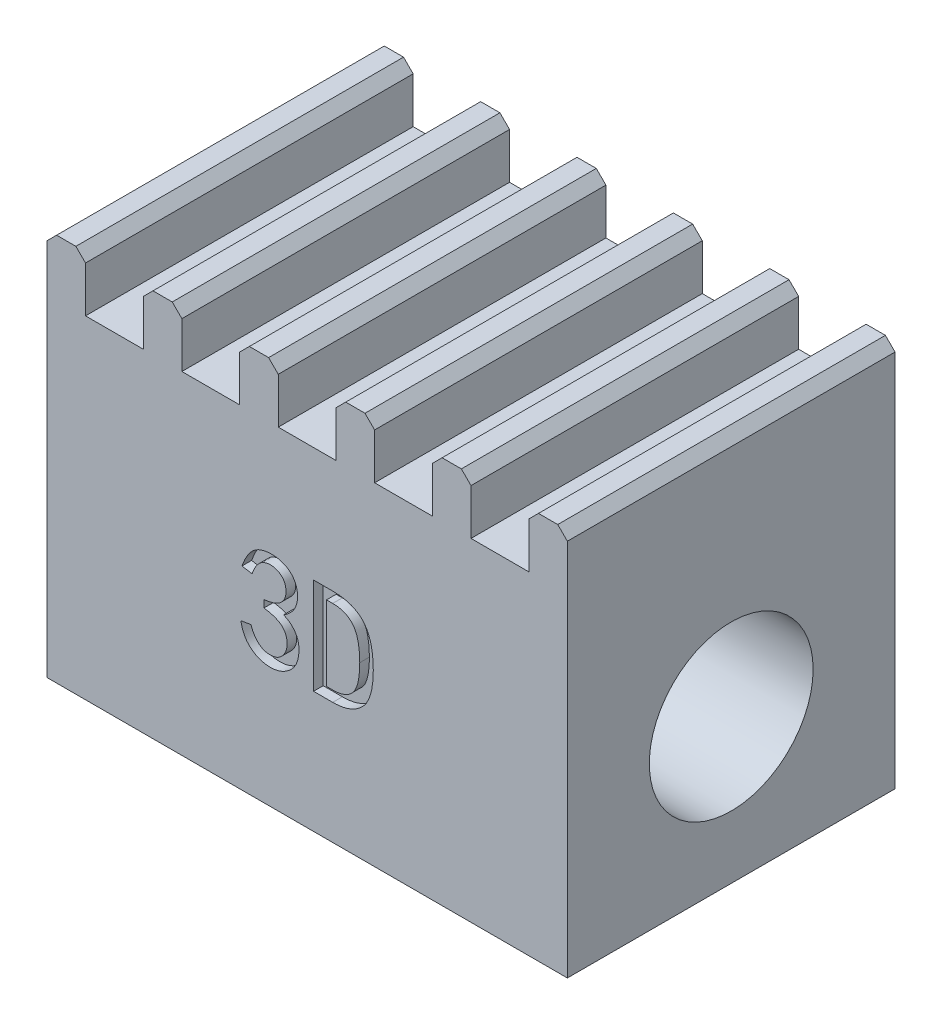
SolidWorks part; units mm, degrees
ref_plane "前视基准面" through (0, 0, 0) normal (0, 0, 1) x (1, 0, 0)
ref_plane "上视基准面" through (0, 0, 0) normal (0, 1, 0) x (1, 0, 0)
ref_plane "右视基准面" through (0, 0, 0) normal (1, 0, 0) x (0, 0, -1)
sketch "草图1" plane through (0, 0, 0) normal (0, 0, 1) x (1, 0, 0)
  line L0 (-5.4, 3.45) -> (-5.4, 4.4)
  line L1 (-5.4, -3.45) -> (5.4, -3.45)
  line L2 (-5.4, -3.45) -> (-5.4, 3.45)
  line L3 (-5.4, 3.45) -> (5.4, 3.45) construction
  line L4 (5.4, -3.45) -> (5.4, 3.45)
  line L5 (-5.4, -3.45) -> (5.4, 3.45) construction
  line L6 (-5.4, 3.45) -> (5.4, -3.45) construction
  line L7 (-5.4, 4.4) -> (-5.2, 4.6)
  line L8 (-5.2, 4.6) -> (-4.8, 4.6)
  line L9 (-4.8, 4.6) -> (-4.6, 4.4)
  line L10 (-4.6, 4.4) -> (-4.6, 3.45)
  line L11 (-4.6, 3.45) -> (-3.4, 3.45)
  line L12 (-1002.6285, 5.45) -> (48997.3715, 5.45) construction
  line L13 (-3.4, 3.45) -> (-3.4, 4.4)
  line L14 (-3.4, 4.4) -> (-3.2, 4.6)
  line L15 (-3.2, 4.6) -> (-2.8, 4.6)
  line L16 (-2.8, 4.6) -> (-2.6, 4.4)
  line L17 (-2.6, 4.4) -> (-2.6, 3.45)
  line L18 (-2.6, 3.45) -> (-1.4, 3.45)
  line L19 (-1.4, 3.45) -> (-1.4, 4.4)
  line L20 (-1.4, 4.4) -> (-1.2, 4.6)
  line L21 (-1.2, 4.6) -> (-0.8, 4.6)
  line L22 (-0.8, 4.6) -> (-0.6, 4.4)
  line L23 (-0.6, 4.4) -> (-0.6, 3.45)
  line L24 (-0.6, 3.45) -> (0.6, 3.45)
  line L25 (0.6, 3.45) -> (0.6, 4.4)
  line L26 (0.6, 4.4) -> (0.8, 4.6)
  line L27 (0.8, 4.6) -> (1.2, 4.6)
  line L28 (1.2, 4.6) -> (1.4, 4.4)
  line L29 (1.4, 4.4) -> (1.4, 3.45)
  line L30 (1.4, 3.45) -> (2.6, 3.45)
  line L31 (2.6, 3.45) -> (2.6, 4.4)
  line L32 (2.6, 4.4) -> (2.8, 4.6)
  line L33 (2.8, 4.6) -> (3.2, 4.6)
  line L34 (3.2, 4.6) -> (3.4, 4.4)
  line L35 (3.4, 4.4) -> (3.4, 3.45)
  line L36 (3.4, 3.45) -> (4.6, 3.45)
  line L37 (4.6, 3.45) -> (4.6, 4.4)
  line L38 (4.6, 4.4) -> (4.8, 4.6)
  line L39 (4.8, 4.6) -> (5.2, 4.6)
  line L40 (5.2, 4.6) -> (5.4, 4.4)
  line L41 (5.4, 4.4) -> (5.4, 3.45)
  line L43 (5.4, 3.45) -> (6.6, 3.45) [skipped]
  point P0 (0, 0)
  dimension "D1" = 6.9
  dimension "D2" = 2
  dimension "D3" = 0.85
  dimension "D4" = 0.2
  dimension "D5" = 0.2
  dimension "D6" = 0.8
  dimension "D7" = 2
  dimension "D8" = 6
extrude "凸台-拉伸1" add sketch "草图1" along normal blind 6.8
sketch "草图2" plane through (5.4, 0, 0) normal (1, 0, 0) x (0, 0, -1)
  line L0 (-6.8, -3.45) -> (-6.8, 4.4) construction
  line L1 (0, -3.45) -> (-7, -3.45)
  line L2 (0, -3.45) -> (0, 2.55)
  line L3 (0, 2.55) -> (-7, 2.55)
  line L4 (-7, -3.45) -> (-7, 2.55)
  circle A0 centre (-3.4, -0.45) radius 1.7
  dimension "D5" = 3.4
  dimension "D1" = 6
  dimension "D2" = 7
  dimension "D3" = 3.4
  dimension "D4" = 3
  dimension "D6" = 6.8
extrude "切除-拉伸1" cut sketch "草图2" against normal blind 4 contours A0
mirror "镜向1" about plane through (0, 0, 0) normal (1, 0, 0) of "切除-拉伸1"
sketch "草图3" plane through (0, 0, 6.8) normal (0, 0, 1) x (1, 0, 0)
  text T0 "3D" font "楷体" height 2
extrude "切除-拉伸2" cut sketch "草图3" against normal blind 0.2
